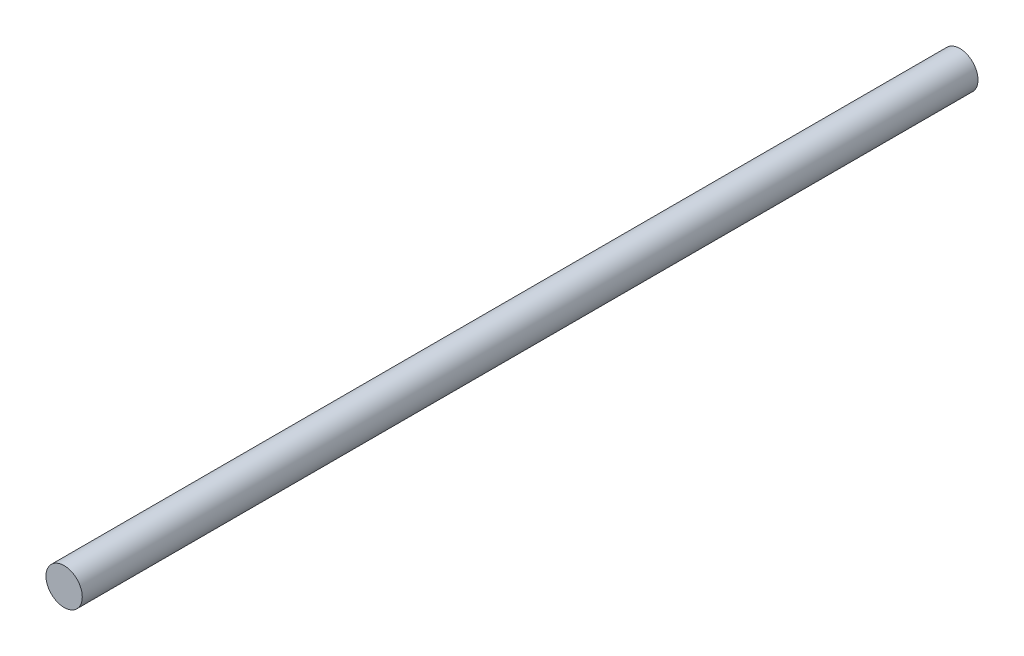
SolidWorks part; units mm, degrees
ref_plane "Plan de face" through (0, 0, 0) normal (0, 0, 1) x (1, 0, 0)
ref_plane "Plan de dessus" through (0, 0, 0) normal (0, 1, 0) x (1, 0, 0)
ref_plane "Plan de droite" through (0, 0, 0) normal (1, 0, 0) x (0, 0, -1)
sketch "Esquisse1" plane through (0, 0, 0) normal (0, 0, 1) x (1, 0, 0)
  circle A0 centre (0, 0) radius 1.5
  dimension "D1" = 3
extrude "Boss.-Extru.1" add sketch "Esquisse1" along normal blind 74
